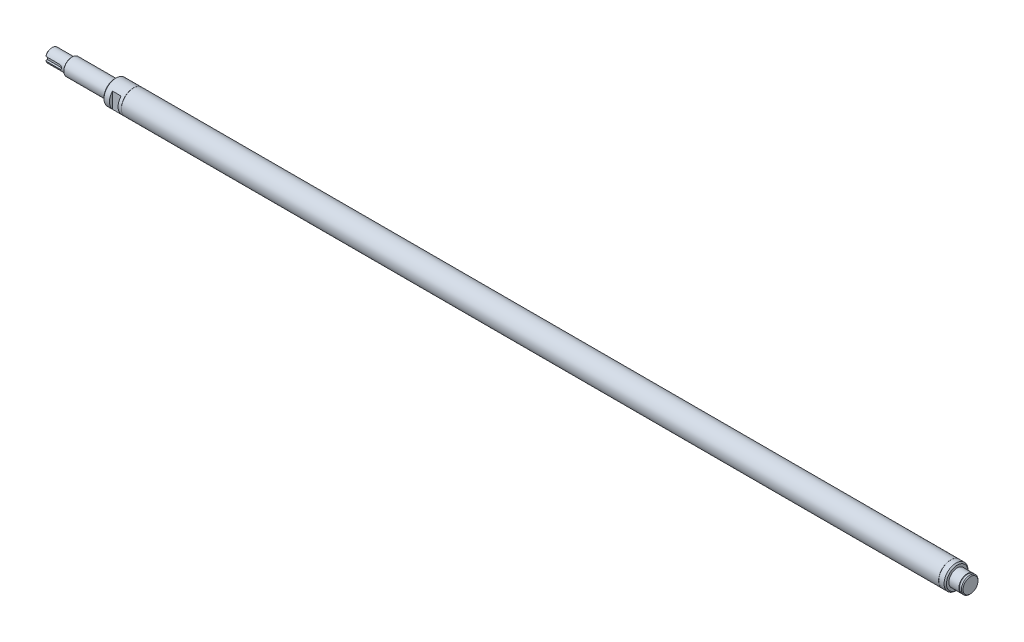
SolidWorks part; units mm, degrees
ref_plane "Front Plane" through (0, 0, 0) normal (0, 0, 1) x (1, 0, 0)
ref_plane "Top Plane" through (0, 0, 0) normal (0, 1, 0) x (1, 0, 0)
ref_plane "Right Plane" through (0, 0, 0) normal (1, 0, 0) x (0, 0, -1)
ref_plane "Plane1" through (0, 0, 0) normal (0, 0, 1) x (1, 0, 0)
sketch "Sketch1" plane through (0, 0, 0) normal (0, 0, 1) x (1, 0, 0)
  line L0 (5, 0) -> (5, 18)
  line L1 (5, 18) -> (1234, 18)
  line L2 (1234, 18) -> (1234, 0)
  line L3 (1234, 0) -> (5, 0)
  line L4 (1234, 0) -> (5, 0) construction
  line L5 (1150, 0) -> (1150, 54.4991) construction
  dimension "D1" = 18
  dimension "D2" = 5
  dimension "D3" = 84
  dimension "D4" = 1145
revolve "Revolve1" add sketch "Sketch1" angle 360 about L4
cosmetic thread "Cosmetic Thread1" parameters "D1"=1229, "D2"=32.319
sketch "Sketch2" plane through (0, 0, 0) normal (0, 0, 1) x (1, 0, 0)
  line L0 (-118, 0) -> (-118, 8.8889)
  line L1 (-118, 8.8889) -> (-116.8889, 10)
  line L2 (-116.8889, 10) -> (-88, 10)
  line L3 (-88, 10) -> (-88, 11.58)
  line L4 (-88, 11.58) -> (-87.08, 12.5)
  line L5 (-87.08, 12.5) -> (-23, 12.5)
  line L6 (-23, 12.5) -> (-23, 16.2)
  line L7 (-23, 16.2) -> (-21.2, 18)
  line L8 (-21.2, 18) -> (4.8, 18)
  line L9 (4.8, 18) -> (4.8, 14.4)
  line L10 (4.8, 14.4) -> (5, 14.4)
  line L11 (5, 14.4) -> (5, 0)
  line L12 (5, 0) -> (-118, 0)
  line L13 (5, 0) -> (-118, 0) construction
  line L14 (5, 18) -> (5, -18) construction
  line L15 (5, 18) -> (5, -18) construction
  dimension "D1" = 0.2
  dimension "D2" = 3.6
  dimension "D3" = 28
  dimension "D4" = 12.5
  dimension "D5" = 10
  dimension "D6" = 93
  dimension "D7" = 123
  dimension "D8" = 45
  dimension "D9" = 1.1111
  dimension "D10" = 0.92
  dimension "D11" = 45
  dimension "D12" = 45
  dimension "D13" = 1.8
revolve "Revolve2" add sketch "Sketch2" angle 360 about L13
cosmetic thread "Cosmetic Thread2" parameters "D1"=18, "D2"=23.16
ref_plane "Plane3" through (0, 0, 13.5) normal (0, 0, 1) x (1, 0, 0)
sketch "Sketch3" plane through (0, 0, 13.5) normal (0, 0, 1) x (1, 0, 0)
  line L0 (-13, -18) -> (0, -18)
  line L1 (0, -18) -> (0, 18)
  line L2 (0, 18) -> (-13, 18)
  line L3 (-13, 18) -> (-13, -18)
extrude "Cut-Extrude1" cut sketch "Sketch3" along normal blind 9
ref_plane "Plane4" through (0, 0, -13.5) normal (0, 0, 1) x (1, 0, 0)
sketch "Sketch4" plane through (0, 0, -13.5) normal (0, 0, 1) x (1, 0, 0)
  line L0 (-13, -18) -> (0, -18)
  line L1 (0, -18) -> (0, 18)
  line L2 (0, 18) -> (-13, 18)
  line L3 (-13, 18) -> (-13, -18)
extrude "Cut-Extrude2" cut sketch "Sketch4" against normal blind 9
ref_plane "Plane5" through (0, 0, 10) normal (0, 0, 1) x (1, 0, 0)
sketch "Sketch5" plane through (0, 0, 10) normal (0, 0, 1) x (1, 0, 0)
  line L0 (-118, -3) -> (-96, -3)
  line L1 (-96, 3) -> (-118, 3)
  line L2 (-118, 3) -> (-118, -3)
  arc A0 (-96, -3) -> (-96, 3) centre (-96, 0) ccw
extrude "Cut-Extrude3" cut sketch "Sketch5" against normal blind 3.5
sketch "Sketch6" plane through (0, 0, 0) normal (0, 0, 1) x (1, 0, 0)
  line L0 (1234, 0) -> (1234, 14.4)
  line L1 (1234, 14.4) -> (1234.2, 14.4)
  line L2 (1234.2, 14.4) -> (1234.2, 18)
  line L3 (1234.2, 18) -> (1242.2, 18)
  line L4 (1242.2, 18) -> (1244, 16.2)
  line L5 (1244, 16.2) -> (1244, 12.5)
  line L6 (1244, 12.5) -> (1259, 12.5)
  line L7 (1259, 12.5) -> (1259, 11.95)
  line L8 (1259, 11.95) -> (1260.35, 11.95)
  line L9 (1260.35, 11.95) -> (1260.35, 12.5)
  line L10 (1260.35, 12.5) -> (1262.75, 12.5)
  line L11 (1262.75, 12.5) -> (1264, 11.25)
  line L12 (1264, 11.25) -> (1264, 0)
  line L13 (1264, 0) -> (1234, 0)
  line L14 (1264, 0) -> (1234, 0) construction
  line L15 (1234, -18) -> (1234, 18) construction
  line L16 (1234, -18) -> (1234, 18) construction
  dimension "D1" = 3.6
  dimension "D2" = 0.2
  dimension "D3" = 1.8
  dimension "D4" = 45
  dimension "D5" = 9.8
  dimension "D7" = 12.5
  dimension "D8" = 30
  dimension "D9" = 15
  dimension "D10" = 1.35
  dimension "D11" = 0.55
  dimension "D12" = 1.25
  dimension "D13" = 45
revolve "Revolve3" add sketch "Sketch6" angle 360 about L14
other "Freeze***"
